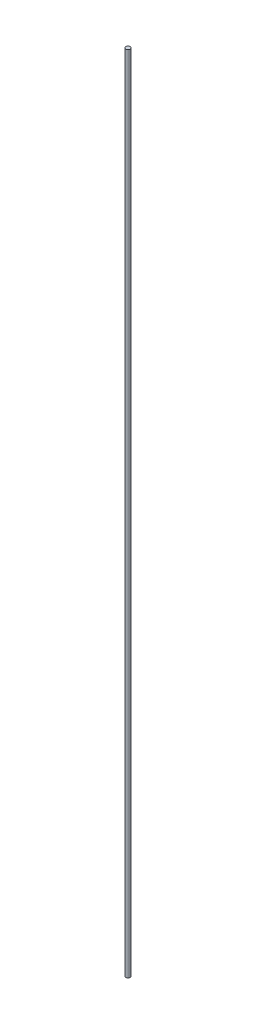
SolidWorks part; units mm, degrees
ref_plane "Front Plane" through (0, 0, 0) normal (0, 0, 1) x (1, 0, 0)
ref_plane "Top Plane" through (0, 0, 0) normal (0, 1, 0) x (1, 0, 0)
ref_plane "Right Plane" through (0, 0, 0) normal (1, 0, 0) x (0, 0, -1)
sketch "Sketch1" plane through (0, 0, 0) normal (0, 1, 0) x (1, 0, 0)
  circle A0 centre (0, 0) radius 0.5
  dimension "D1" = 1
extrude "Boss-Extrude1" add sketch "Sketch1" along normal blind 180
